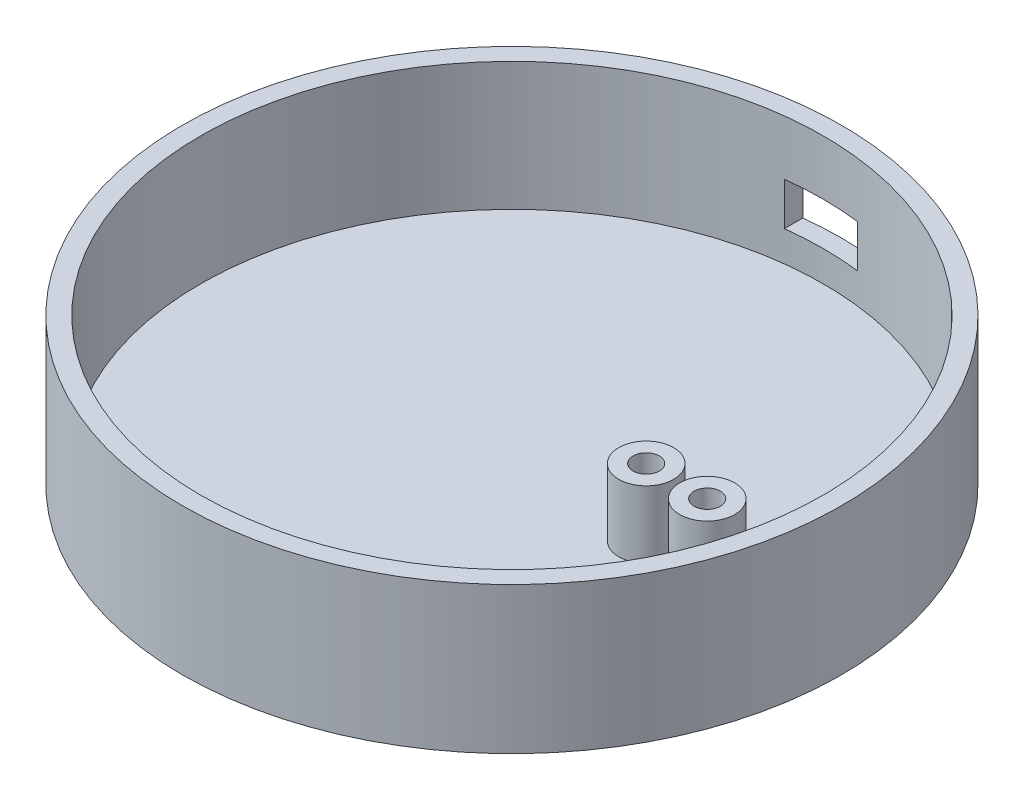
SolidWorks part; units mm, degrees
ref_plane "前视基准面" through (0, 0, 0) normal (0, 0, 1) x (1, 0, 0)
ref_plane "上视基准面" through (0, 0, 0) normal (0, 1, 0) x (1, 0, 0)
ref_plane "右视基准面" through (0, 0, 0) normal (1, 0, 0) x (0, 0, -1)
other "Configuration Table"
sketch "草图1" plane through (0, 0, 0) normal (0, 1, 0) x (1, 0, 0)
  circle A0 centre (0, 0) radius 54
extrude "Floor_D108_T3" add sketch "草图1" along normal blind 3
sketch "草图2" plane through (0, 0, 0) normal (0, 1, 0) x (1, 0, 0)
  circle A0 centre (0, 0) radius 54
  circle A1 centre (0, 0) radius 51
extrude "Rim_OD108_ID102_H24" add sketch "草图2" along normal blind 24
sketch "草图3" plane through (0, 0, 0) normal (0, 1, 0) x (1, 0, 0)
  circle A0 centre (22, 0) radius 4.5
  circle A1 centre (32, 0) radius 4.5
extrude "Sensor_fixed_posts" add sketch "草图3" along normal blind 14
sketch "草图4" plane through (0, 0, 0) normal (0, 1, 0) x (1, 0, 0)
  circle A0 centre (22, 0) radius 2.15
  circle A1 centre (32, 0) radius 2.15
extrude "M4_fixed_mount_clearance" cut sketch "草图4" along normal blind 14
ref_plane "基准面1" through (0, 8, 0) normal (0, 1, 0) x (1, 0, 0)
sketch "草图5" plane through (0, 8, 0) normal (0, 1, 0) x (1, 0, 0)
  line L1 (-6, 49) -> (6, 49)
  line L2 (-6, 49) -> (-6, 60)
  line L3 (-6, 60) -> (6, 60)
  line L4 (6, 49) -> (6, 60)
extrude "USB_C_side_opening_12x7" cut sketch "草图5" along normal blind 7
